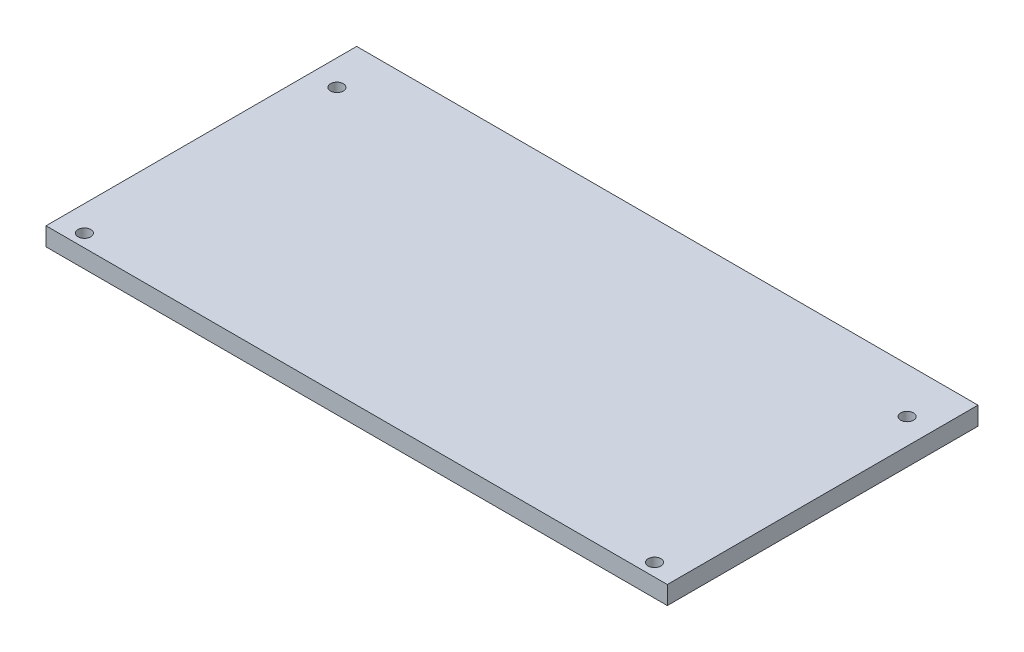
SolidWorks part; units mm, degrees
ref_plane "前视基准面" through (0, 0, 0) normal (0, 0, 1) x (1, 0, 0)
ref_plane "上视基准面" through (0, 0, 0) normal (0, 1, 0) x (1, 0, 0)
ref_plane "右视基准面" through (0, 0, 0) normal (1, 0, 0) x (0, 0, -1)
sketch "草图2" plane through (0, 0, 0) normal (0, 1, 0) x (1, 0, 0)
  line L1 (-48.0628, 28.7042) -> (121.9372, 28.7042)
  line L2 (-48.0628, 28.7042) -> (-48.0628, -56.2958)
  line L3 (-48.0628, -56.2958) -> (121.9372, -56.2958)
  line L4 (121.9372, 28.7042) -> (121.9372, -56.2958)
  line L5 (-48.0628, 28.7042) -> (121.9372, -56.2958) construction
  line L6 (-48.0628, -56.2958) -> (121.9372, 28.7042) construction
  point P4 (36.9372, -13.7958)
  dimension "D1" = 170
  dimension "D2" = 85
extrude "凸台-拉伸1" add sketch "草图2" along normal blind 5
sketch "草图4" plane through (0, 0, 0) normal (0, -1, 0) x (1, 0, 0)
  circle A0 centre (-41.0628, 52.7958) radius 1.75
  circle A1 centre (-41.0628, -16.3004) radius 1.75
  circle A2 centre (114.9372, -16.3004) radius 1.75
  circle A3 centre (114.9372, 52.7958) radius 1.75
extrude "切除-拉伸1" cut sketch "草图4" against normal through all
